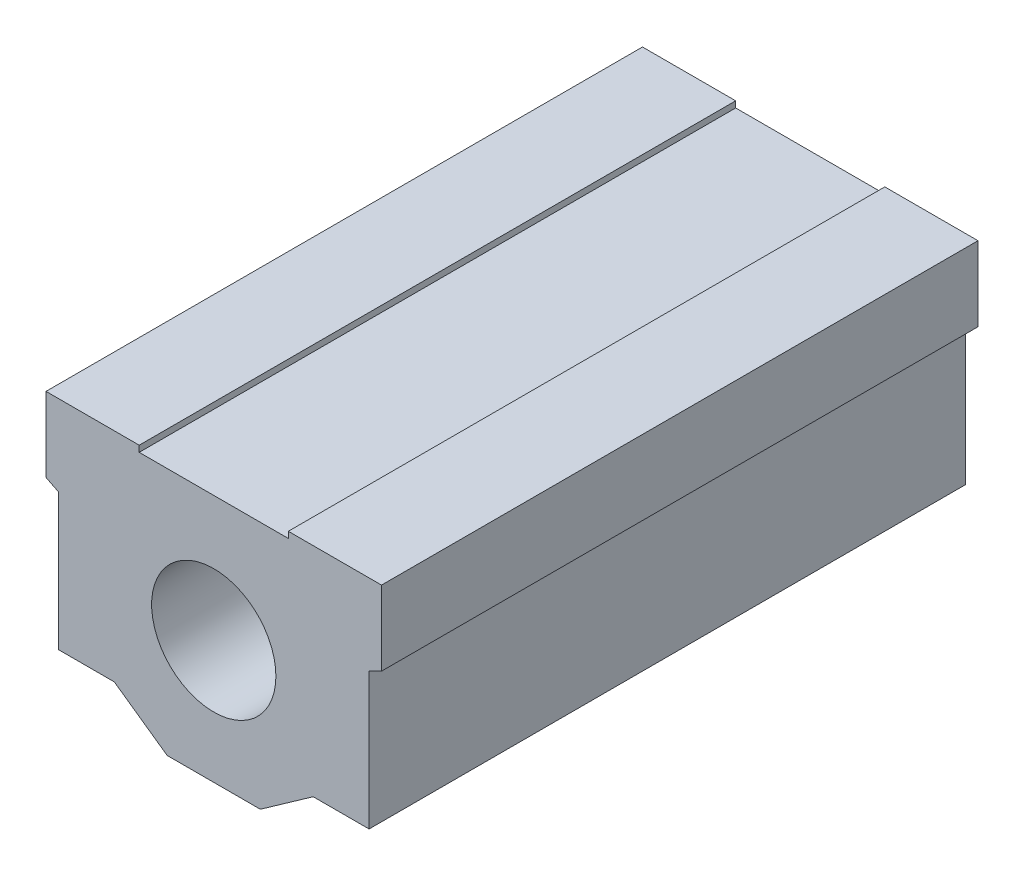
SolidWorks part; units mm, degrees
ref_plane "前视基准面" through (0, 0, 0) normal (0, 0, 1) x (1, 0, 0)
ref_plane "上视基准面" through (0, 0, 0) normal (0, 1, 0) x (1, 0, 0)
ref_plane "右视基准面" through (0, 0, 0) normal (1, 0, 0) x (0, 0, -1)
sketch "草图1" plane through (0, 0, 0) normal (0, 0, 1) x (1, 0, 0)
  line L0 (0, 42.0934) -> (0, 0) construction
  line L1 (0, 0) -> (49.8045, 0) construction
  line L2 (7.5, 0) -> (-7.5, 0)
  line L3 (-7.5, 0) -> (-16, 6)
  line L4 (-16, 6) -> (-25, 6)
  line L5 (-25, 6) -> (-25, 28)
  line L6 (-25, 28) -> (-27, 29)
  line L7 (-27, 29) -> (-27, 41)
  line L8 (-27, 41) -> (-12, 41)
  line L9 (-12, 41) -> (-12, 40)
  line L10 (-12, 40) -> (12, 40)
  line L11 (16, 6) -> (25, 6)
  line L12 (7.5, 0) -> (16, 6)
  line L13 (25, 28) -> (27, 29)
  line L14 (25, 6) -> (25, 28)
  line L15 (27, 29) -> (27, 41)
  line L16 (12, 41) -> (12, 40)
  line L17 (27, 41) -> (12, 41)
  circle A0 centre (0, 19.8) radius 10
  point P23 (0, 40)
  dimension "D1" = 20
  dimension "D2" = 54
  dimension "D3" = 41
  dimension "D4" = 19.8
  dimension "D5" = 50
  dimension "D6" = 15
  dimension "D7" = 24
  dimension "D8" = 1
  dimension "D9" = 35
  dimension "D10" = 9
  dimension "D11" = 22
  dimension "D12" = 12
extrude "凸台-拉伸1" add sketch "草图1" along normal blind 96
